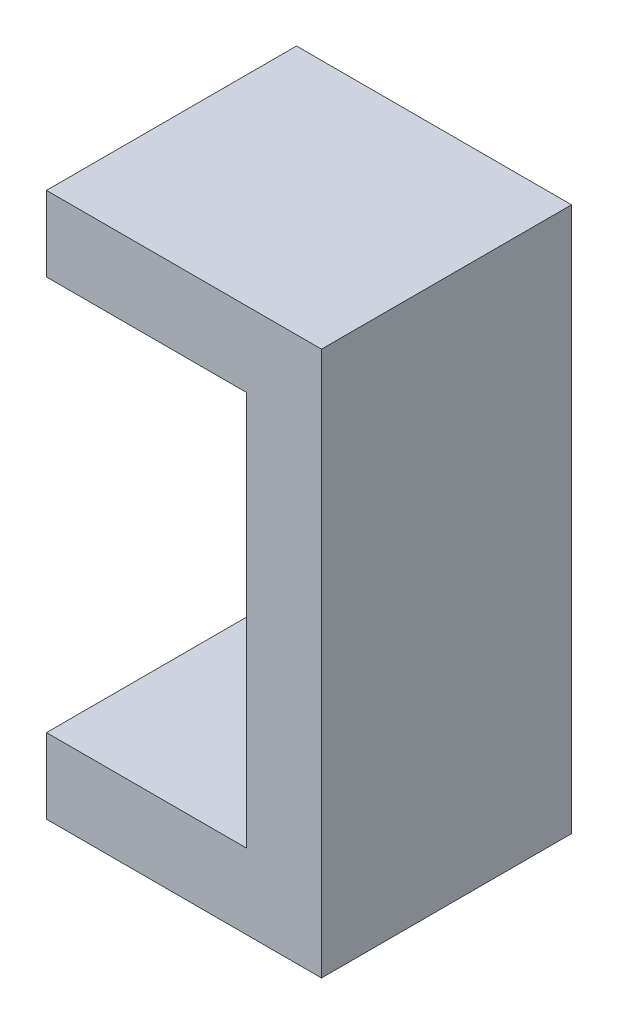
SolidWorks part; units mm, degrees
ref_plane "Front Plane" through (0, 0, 0) normal (0, 0, 1) x (1, 0, 0)
ref_plane "Top Plane" through (0, 0, 0) normal (0, 1, 0) x (1, 0, 0)
ref_plane "Right Plane" through (0, 0, 0) normal (1, 0, 0) x (0, 0, -1)
sketch "Sketch1" plane through (0, -13.5255, 0) normal (0, -1, 0) x (1, 0, 0)
  line L0 (5.08, 3.175) -> (5.08, -66.675) construction
  line L1 (8.128, -3.2691) -> (-3.048, -3.2691)
  line L2 (8.128, -3.2691) -> (8.128, -13.4291)
  line L3 (8.128, -13.4291) -> (-3.048, -13.4291)
  line L4 (-3.048, -3.2691) -> (-3.048, -13.4291)
  dimension "D1" = 11.176
  dimension "D2" = 3.048
  dimension "D3" = 10.16
extrude "Boss-Extrude1" add sketch "Sketch1" along normal blind 3.048
sketch "Sketch2" plane through (0, -13.5255, 0) normal (0, 1, 0) x (1, 0, 0)
  line L0 (5.08, -3.175) -> (5.08, 66.675) construction
  line L1 (8.128, 3.2691) -> (5.08, 3.2691)
  line L2 (8.128, 3.2691) -> (8.128, 13.4291)
  line L3 (8.128, 13.4291) -> (5.08, 13.4291)
  line L4 (5.08, 3.2691) -> (5.08, 13.4291)
  line L5 (-3.048, 13.4291) -> (8.128, 13.4291) construction
extrude "Boss-Extrude2" add sketch "Sketch2" along normal offset from surface (19.0815 mm away) 3.556
sketch "Sketch3" plane through (5.08, 0, 0) normal (-1, 0, 0) x (0, 0, 1)
  line L0 (-3.2691, 5.556) -> (-3.2691, -13.5255) construction
  line L1 (-13.4291, 5.556) -> (-3.2691, 5.556)
  line L2 (-13.4291, 5.556) -> (-13.4291, 2.508)
  line L3 (-13.4291, 2.508) -> (-3.2691, 2.508)
  line L4 (-3.2691, 5.556) -> (-3.2691, 2.508)
  line L5 (-61.595, 2) -> (-1.905, 2) construction
  dimension "D1" = 0.508
extrude "Boss-Extrude3" add sketch "Sketch3" along normal up to surface (8.128 mm away) up to face at (-3.048, -15.0495, -8.3491)
sketch "Sketch4" plane through (0, 2.508, 0) normal (0, -1, 0) x (1, 0, 0)
  line L0 (-3.048, -13.4291) -> (8.128, -13.4291) construction
  line L1 (-3.048, -3.2691) -> (0, -3.2691)
  line L2 (-3.048, -3.2691) -> (-3.048, -13.4291)
  line L3 (-3.048, -13.4291) -> (0, -13.4291)
  line L4 (0, -3.2691) -> (0, -13.4291)
  line L5 (0, 0) -> (0, -63.5) construction
extrude "Boss-Extrude4" add sketch "Sketch4" along normal blind 1.27 draft 45
